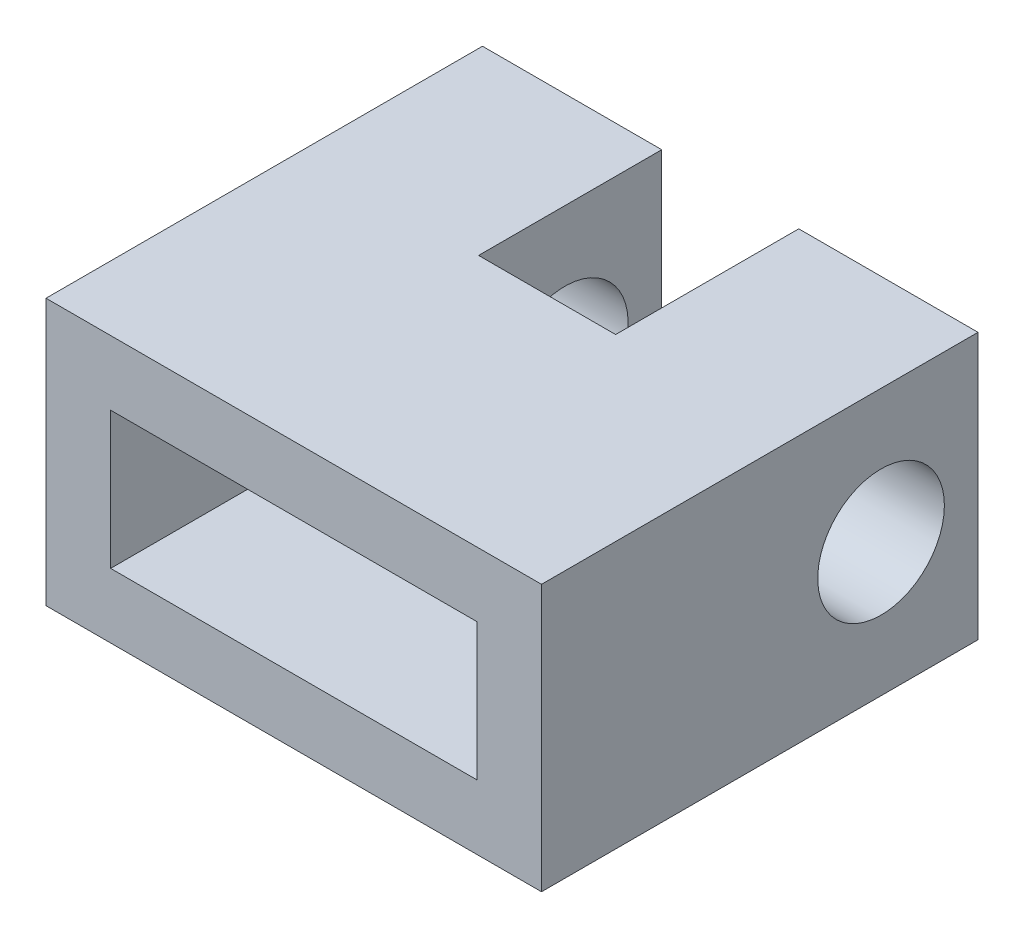
SolidWorks part; units mm, degrees
ref_plane "Front Plane" through (0, 0, 0) normal (0, 0, 1) x (1, 0, 0)
ref_plane "Top Plane" through (0, 0, 0) normal (0, 1, 0) x (1, 0, 0)
ref_plane "Right Plane" through (0, 0, 0) normal (1, 0, 0) x (0, 0, -1)
sketch "Sketch1" plane through (0, 0, 0) normal (0, 0, 1) x (1, 0, 0)
  line L1 (0, 0) -> (8.5, 0)
  line L2 (0, 0) -> (0, 3.18)
  line L3 (0, 3.18) -> (8.5, 3.18)
  line L4 (8.5, 0) -> (8.5, 3.18)
  line L5 (-1.5, 4.68) -> (10, 4.68)
  line L6 (-1.5, 4.68) -> (-1.5, -1.5)
  line L7 (-1.5, -1.5) -> (10, -1.5)
  line L8 (10, 4.68) -> (10, -1.5)
  point P9 (4.8803, 3.9838)
  dimension "D1" = 3.18
  dimension "D2" = 8.5
  dimension "D3" = 1.5
  dimension "D4" = 1.5
  dimension "D5" = 1.5
  dimension "D6" = 1.5
extrude "Boss-Extrude1" add sketch "Sketch1" along normal blind 4.88
sketch "Sketch2" plane through (0, 0, 0) normal (0, 0, -1) x (-1, 0, 0)
  line L1 (-10, 4.68) -> (1.5, 4.68)
  line L2 (-10, 4.68) -> (-10, -1.5)
  line L3 (-10, -1.5) -> (1.5, -1.5)
  line L4 (1.5, 4.68) -> (1.5, -1.5)
extrude "Boss-Extrude2" add sketch "Sketch2" along normal blind 1
sketch "Sketch3" plane through (0, 0, -1) normal (0, 0, -1) x (-1, 0, 0)
  line L1 (-10, 4.68) -> (-5.84, 4.68)
  line L2 (-10, 4.68) -> (-10, -1.5)
  line L3 (-10, -1.5) -> (-5.84, -1.5)
  line L4 (-5.84, 4.68) -> (-5.84, -1.5)
  line L6 (-2.66, -1.5) -> (1.5, -1.5)
  line L7 (-2.66, -1.5) -> (-2.66, 4.68)
  line L8 (-2.66, 4.68) -> (1.5, 4.68)
  line L9 (1.5, -1.5) -> (1.5, 4.68)
  point P5 (0, 0)
  point P6 (1.054, -1.1403)
  dimension "D1" = 3.18
extrude "Boss-Extrude3" add sketch "Sketch3" along normal up to surface (4.25 mm away)
sketch "Sketch4" plane through (10, 0, 0) normal (1, 0, 0) x (0, 0, -1)
  line L0 (5.25, 1.59) -> (-4.88, 1.59) construction
  line L1 (5.25, 4.68) -> (5.25, -1.5) construction
  line L2 (-4.88, -1.5) -> (-4.88, 4.68) construction
  line L3 (1, -42.5561) -> (1, 7.4439) construction
  circle A0 centre (3, 1.59) radius 1.47
  dimension "D1" = 2
  dimension "D2" = 2.94
extrude "Cut-Extrude1" cut sketch "Sketch4" against normal blind 7.5
sketch "Sketch5" plane through (-1.5, 0, 0) normal (-1, 0, 0) x (0, 0, 1)
  line L0 (-5.25, 1.59) -> (4.88, 1.59) construction
  line L1 (-5.25, -1.5) -> (-5.25, 4.68) construction
  line L2 (4.88, 4.68) -> (4.88, -1.5) construction
  line L3 (-1, 7.5261) -> (-1, -42.4739) construction
  circle A0 centre (-3, 1.59) radius 1.47
  dimension "D2" = 2.94
  dimension "D1" = 2
extrude "Cut-Extrude2" cut sketch "Sketch5" against normal through all
